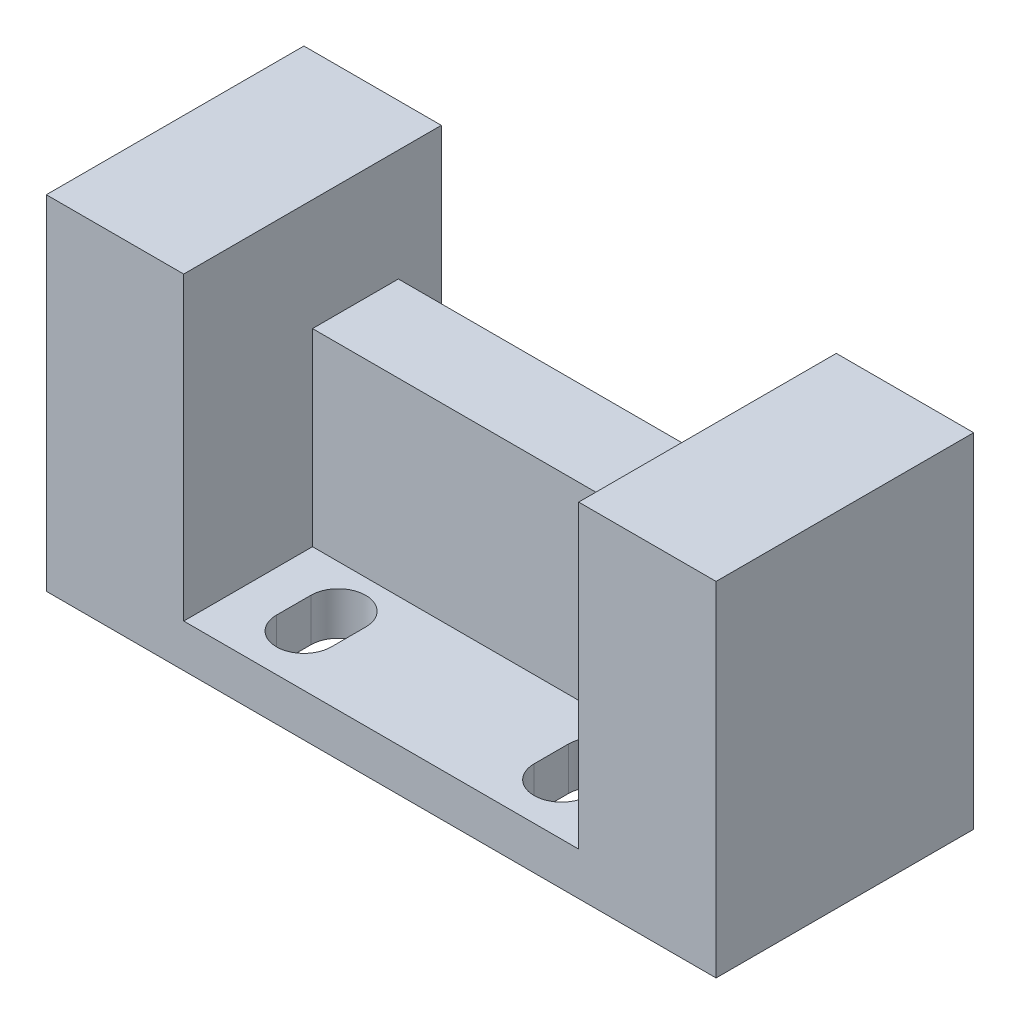
SolidWorks part; units mm, degrees
ref_plane "前视基准面" through (0, 0, 0) normal (0, 0, 1) x (1, 0, 0)
ref_plane "上视基准面" through (0, 0, 0) normal (0, 1, 0) x (1, 0, 0)
ref_plane "右视基准面" through (0, 0, 0) normal (1, 0, 0) x (0, 0, -1)
other "Configuration Table"
sketch "草图1" plane through (0, 0, 0) normal (0, 0, 1) x (1, 0, 0)
  line L0 (19.5, 21) -> (19.5, -0.4188) construction
  line L1 (0, 0) -> (8, 0)
  line L2 (0, 0) -> (0, 20)
  line L3 (0, 20) -> (8, 20)
  line L4 (8, 0) -> (8, 20)
  line L5 (31, 0) -> (39, 0)
  line L6 (31, 0) -> (31, 20)
  line L7 (31, 20) -> (39, 20)
  line L8 (39, 0) -> (39, 20)
  dimension "D1" = 8
  dimension "D2" = 20
  dimension "D3" = 8
  dimension "D4" = 20
  dimension "D5" = 39
  dimension "D6" = 19.5
  dimension "D7" = 0
extrude "凸台-拉伸1" add sketch "草图1" along normal blind 10
sketch "草图2" plane through (0, 0, 0) normal (0, -1, 0) x (1, 0, 0)
  line L0 (39, 10) -> (39, 0) construction
  line L1 (0, 0) -> (39, 0)
  line L2 (0, 0) -> (0, 15)
  line L3 (0, 15) -> (39, 15)
  line L4 (39, 0) -> (39, 15)
  dimension "D1" = 0
  dimension "D2" = 15
extrude "凸台-拉伸2" add sketch "草图2" against normal blind 2.5
chamfer "倒角1" distance 1 angle 45 1 edges at (19.5, 2.5, 0)
sketch "草图3" plane through (0, 0, 0) normal (0, 0, -1) x (-1, 0, 0)
  line L0 (-39, 20) -> (-31, 20) construction
  line L1 (-35.5, 17) -> (-3.5, 17) construction
  line L2 (-8, 1.5) -> (-31, 1.5) construction
  line L3 (-35.5, 4) -> (-3.5, 4) construction
  circle A0 centre (-35.5, 17) radius 2
  circle A1 centre (-3.5, 17) radius 2
  circle A2 centre (-35.5, 4) radius 2
  circle A3 centre (-3.5, 4) radius 2
  point P4 (-19.5, 17)
  point P9 (-19.5, 1.5)
  dimension "D1" = 4
  dimension "D5" = 2
  dimension "D2" = 0
  dimension "D3" = 3
  dimension "D4" = 2
extrude "切除-拉伸1" cut sketch "草图3" against normal blind 10
sketch "草图5" plane through (0, 2.5, 0) normal (0, 1, 0) x (1, 0, 0)
  line L0 (12, -12) -> (27, -12) construction
  line L1 (31, -1) -> (8, -1) construction
  line L2 (8, 0) -> (31, 0) construction
  line L3 (12, -12) -> (12, -10) construction
  line L4 (10.4, -12) -> (10.4, -10)
  line L5 (13.6, -12) -> (13.6, -10)
  line L6 (27, -12) -> (27, -10) construction
  line L7 (25.4, -12) -> (25.4, -10)
  line L8 (28.6, -12) -> (28.6, -10)
  arc A2 (10.4, -12) -> (13.6, -12) centre (12, -12) ccw
  arc A3 (13.6, -10) -> (10.4, -10) centre (12, -10) ccw
  arc A4 (25.4, -12) -> (28.6, -12) centre (27, -12) ccw
  arc A5 (28.6, -10) -> (25.4, -10) centre (27, -10) ccw
  point P2 (19.5, -12)
  point P5 (19.5, -1)
  point P6 (12, -11)
  point P14 (27, -11)
  dimension "D3" = 3.2
  dimension "D4" = 2
  dimension "D6" = 3.2
  dimension "D1" = 0
  dimension "D2" = 15
  dimension "D5" = 12
  dimension "D7" = 2
extrude "切除-拉伸3" cut sketch "草图5" against normal blind 10
sketch "草图6" plane through (39, 0, 0) normal (1, 0, 0) x (0, 0, -1)
  line L0 (-10, 20) -> (-10, 2.5)
  line L1 (-10, 2.5) -> (-15, 2.5)
  line L3 (-15, 2.5) -> (-15, 20)
  line L4 (-15, 20) -> (-10, 20)
extrude "凸台-拉伸3" add sketch "草图6" against normal up to surface (8 mm away) up to face at (31, 9.3, 4.2)
sketch "草图7" plane through (0, 0, 0) normal (-1, 0, 0) x (0, 0, 1)
  line L0 (10, 20) -> (10, 2.5)
  line L1 (10, 2.5) -> (15, 2.5)
  line L3 (15, 2.5) -> (15, 20)
  line L4 (15, 20) -> (10, 20)
extrude "凸台-拉伸4" add sketch "草图7" against normal up to surface (8 mm away) up to face at (8, 9.3, 4.2)
sketch "草图8" plane through (31, 0, 0) normal (-1, 0, 0) x (0, 0, 1)
  line L0 (15, 2.5) -> (1, 2.5) construction
  line L1 (2.5, 2.5) -> (7.5, 2.5)
  line L2 (2.5, 2.5) -> (2.5, 13.5)
  line L3 (2.5, 13.5) -> (7.5, 13.5)
  line L4 (7.5, 2.5) -> (7.5, 13.5)
  line L5 (10, 0) -> (10, 2.5) construction
  point P6 (5, 2.5)
  dimension "D1" = 5
  dimension "D2" = 5
  dimension "D3" = 11
extrude "凸台-拉伸5" add sketch "草图8" along normal up to next
